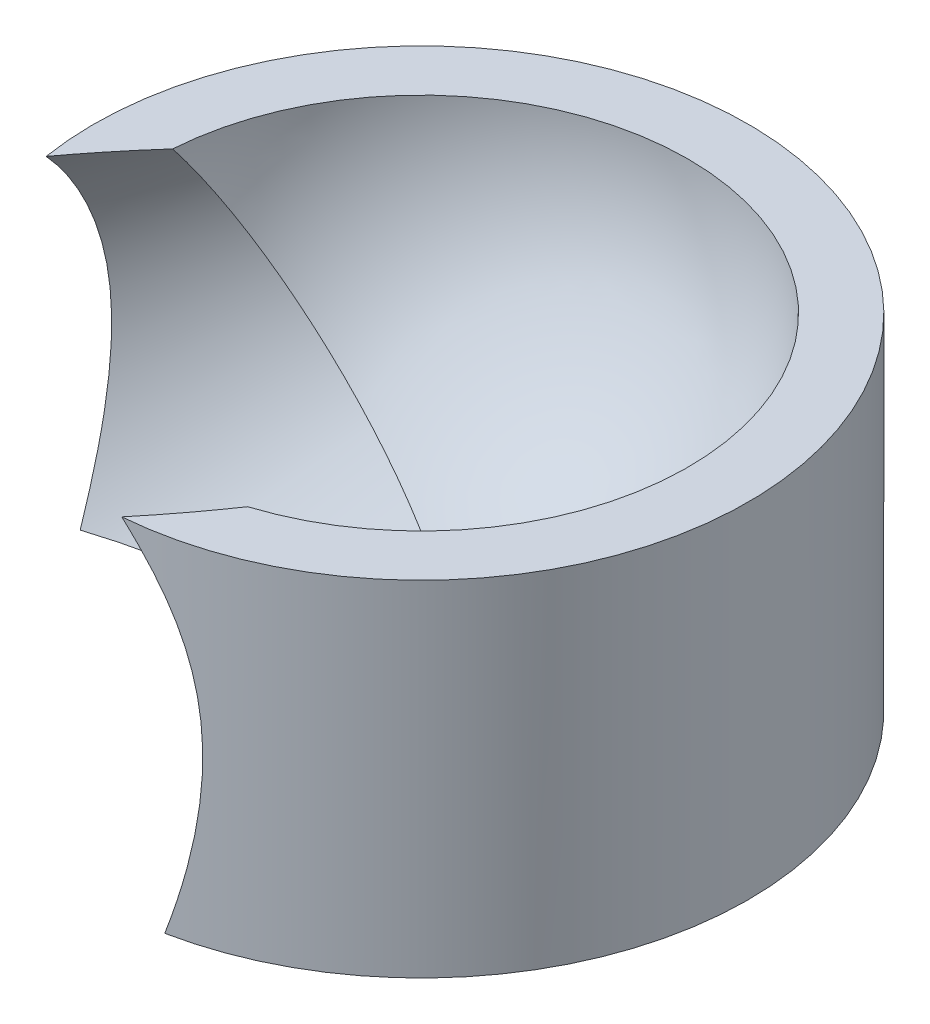
SolidWorks part; units mm, degrees
other "Moving Steel Cup Liner 2"
other "Moving Steel Cup Liner 2 Left"
ref_plane "Front Plane" through (0, 0, 0) normal (0, 0, 1) x (1, 0, 0)
ref_plane "Top Plane" through (0, 0, 0) normal (0, 1, 0) x (1, 0, 0)
ref_plane "Right Plane" through (0, 0, 0) normal (1, 0, 0) x (0, 0, -1)
sketch3d "Keyed Back Sketch datum points"
  point P0 (-56.2917, -97, 0)
  point P1 (-46.2917, -97, 0)
  point P2 (-56.2917, -97, 10)
ref_plane "Keyed Back Sketch plane" through (0, -97, 0) normal (0, -1, 0) x (-1, 0, 0)
sketch "Keyed Back Sketch" plane through (0, -97, 0) normal (0, -1, 0) x (-1, 0, 0)
  line L0 (29.791, 11.2357) -> (33.8308, 13.5681)
  arc A0 (33.8308, 13.5681) -> (29.791, 11.2357) centre (30.3109, 15) ccw
extrude "Keyed Back" add sketch "Keyed Back Sketch" along normal blind 0.7 separate body
sketch3d "Cup Blank Sketch datum points"
  point P0 (-56.2917, -97.7, 0)
  point P1 (-46.2917, -97.7, 0)
  point P2 (-56.2917, -97.7, 10)
ref_plane "Cup Blank Sketch plane" through (0, -97.7, 0) normal (0, -1, 0) x (-1, 0, 0)
sketch "Cup Blank Sketch" plane through (0, -97.7, 0) normal (0, -1, 0) x (-1, 0, 0)
  circle A0 centre (30.3109, 15) radius 3.8
extrude "Cup Blank" add sketch "Cup Blank Sketch" along normal blind 3.3
sketch3d "Spherical Bearing Seat axis line"
  line L0 (-30.3109, -101, -25) -> (-30.3109, -101, -5) construction
ref_axis "Spherical Bearing Seat axis" through (-30.3109, -101, -25) along (0, 0, 1)
sketch3d "Spherical Bearing Seat profile datum points"
  point P0 (-30.3109, -101, -15)
  point P1 (-20.3109, -101, -15)
  point P2 (-30.3109, -101, -5)
ref_plane "Spherical Bearing Seat profile plane" through (0, -101, 0) normal (0, -1, 0) x (-1, 0, 0)
sketch "Spherical Bearing Seat profile" plane through (0, -101, 0) normal (0, -1, 0) x (-1, 0, 0)
  line L0 (30.3109, 11.9) -> (30.3109, 18.1)
  arc A0 (30.3109, 18.1) -> (30.3109, 11.9) centre (30.3109, 15) ccw
revolve "Spherical Bearing Seat" cut sketch "Spherical Bearing Seat profile" angle 360 about axis through (-30.3109, -101, -25) along (0, 0, 1)
sketch3d "Articulation Throat axis line"
  line L0 (-25.111, -106.3831, -21.632) -> (-35.5108, -95.6169, -8.368) construction
ref_axis "Articulation Throat axis" through (-25.111, -106.3831, -21.632) along (-0.52, 0.5383, 0.6632)
sketch3d "Articulation Throat Sketch datum points"
  point P0 (-30.3109, -101, -15)
  point P1 (-30.3109, -93.2358, -21.3021)
  point P2 (-35.5108, -95.6169, -8.368)
ref_plane "Articulation Throat Sketch plane" through (-55.5594, -21.3154, -26.2607) normal (0.8542, 0.3277, 0.4037) x (0.3769, 0.1446, -0.9149)
sketch "Articulation Throat Sketch" plane through (-55.5594, -21.3154, -26.2607) normal (0.8542, 0.3277, 0.4037) x (0.3769, 0.1446, -0.9149)
  line L0 (-12.3085, -83.4412) -> (-10.7241, -81.7739)
  line L1 (-10.7241, -81.7739) -> (-22.7679, -61.059)
  line L2 (-22.7679, -61.059) -> (-28.9813, -67.5977)
  line L3 (-28.9813, -67.5977) -> (-12.3085, -83.4412)
revolve "Articulation Throat" cut sketch "Articulation Throat Sketch" angle 360 about axis through (-25.111, -106.3831, -21.632) along (-0.52, 0.5383, 0.6632)
sketch3d "Mirror1 profile datum points"
  point P0 (0, 0, 0)
  point P1 (10, 0, 0)
  point P2 (0, 0, 10)
ref_plane "Mirror1 profile plane" through (0, 0, 0) normal (0, -1, 0) x (-1, 0, 0)
mirror "Mirror1" about plane through (0, 0, 0) normal (0, -1, 0) of bodies 104
delete or keep bodies "Remove1" type delete bodies bodies 104
